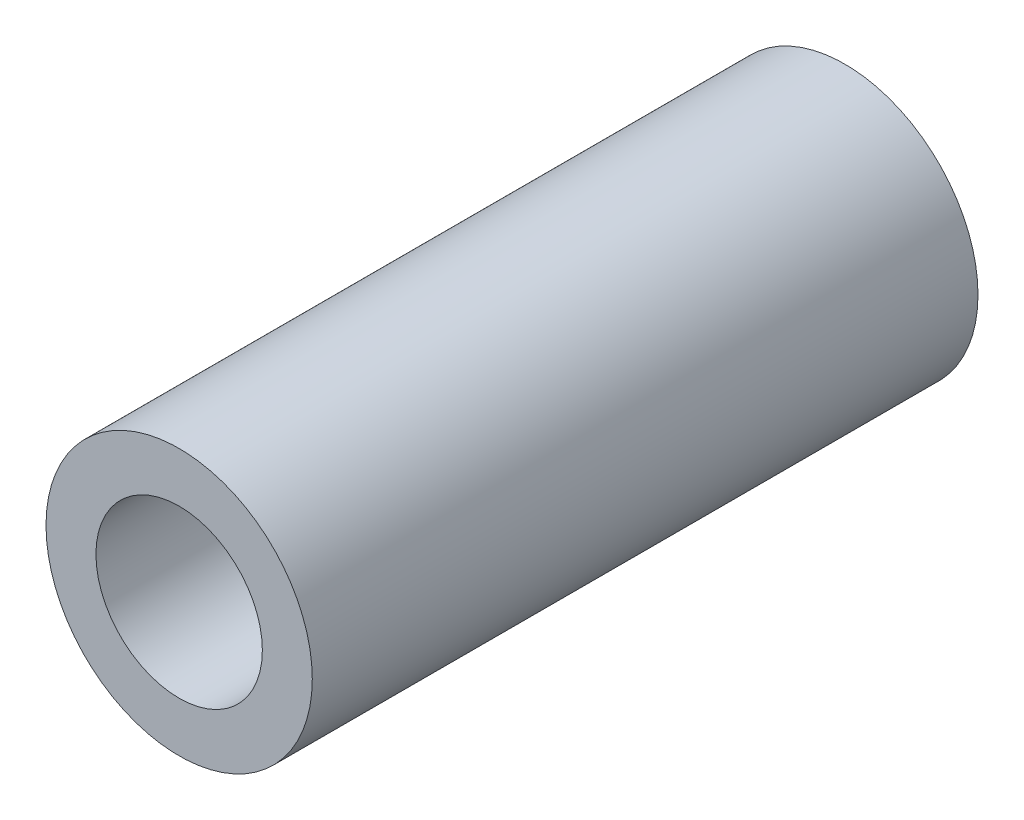
SolidWorks part; units mm, degrees
ref_plane "Alzado" through (0, 0, 0) normal (0, 0, 1) x (1, 0, 0)
ref_plane "Planta" through (0, 0, 0) normal (0, 1, 0) x (1, 0, 0)
ref_plane "Vista lateral" through (0, 0, 0) normal (1, 0, 0) x (0, 0, -1)
sketch "Croquis1" plane through (0, 0, 0) normal (0, 0, 1) x (1, 0, 0)
  circle A0 centre (0, 0) radius 2.5
  circle A1 centre (0, 0) radius 4
  dimension "D1" = 8
  dimension "D2" = 5
extrude "Saliente-Extruir1" add sketch "Croquis1" along normal blind 20
